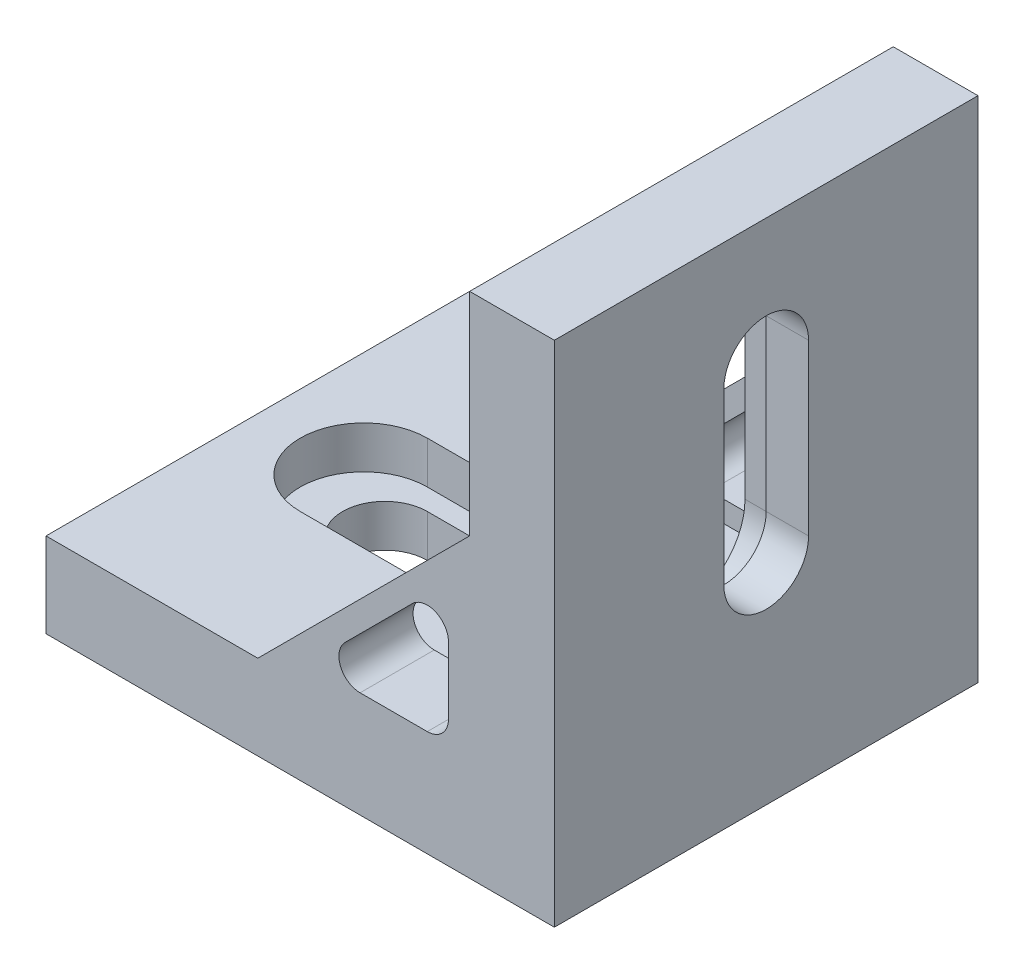
SolidWorks part; units mm, degrees
ref_plane "Front Plane" through (0, 0, 0) normal (0, 0, 1) x (1, 0, 0)
ref_plane "Top Plane" through (0, 0, 0) normal (0, 1, 0) x (1, 0, 0)
ref_plane "Right Plane" through (0, 0, 0) normal (1, 0, 0) x (0, 0, -1)
sketch "Sketch1" plane through (0, 0, 0) normal (0, 1, 0) x (1, 0, 0)
  line L0 (0, 10) -> (0, 0) construction
  line L1 (-10, -10) -> (10, -10)
  line L2 (-10, -10) -> (-10, 10)
  line L3 (-10, 10) -> (10, 10)
  line L4 (10, -10) -> (10, 10)
  line L5 (-10, -10) -> (10, 10) construction
  line L6 (-10, 10) -> (10, -10) construction
  line L7 (-4, 0) -> (4, 0) construction
  line L8 (-4, 2) -> (4, 2)
  line L9 (-4, -2) -> (4, -2)
  arc A0 (-4, 2) -> (-4, -2) centre (-4, 0) ccw
  arc A1 (4, -2) -> (4, 2) centre (4, 0) ccw
  point P0 (0, 0)
  point P10 (0, 0)
  dimension "D4" = 2
  dimension "D1" = 20
  dimension "D2" = 20
  dimension "D3" = 8
extrude "Boss-Extrude1" add sketch "Sketch1" along normal blind 4
sketch "Sketch3" plane through (0, 4, 0) normal (0, 1, 0) x (1, 0, 0)
  line L0 (-5, 0) -> (5, 0) construction
  line L1 (-5, 3) -> (5, 3)
  line L2 (-5, -3) -> (5, -3)
  arc A0 (-5, 3) -> (-5, -3) centre (-5, 0) ccw
  arc A1 (5, -3) -> (5, 3) centre (5, 0) ccw
  point P2 (0, 0)
  dimension "D2" = 3
  dimension "D1" = 10
extrude "Cut-Extrude1" cut sketch "Sketch3" against normal blind 2
sketch "Sketch4" plane through (10, 0, 0) normal (1, 0, 0) x (0, 0, -1)
  line L0 (0, 0) -> (0, 4) construction
  line L1 (-10, 4) -> (10, 4) construction
  line L3 (-10, 0) -> (10, 0)
  line L4 (-10, 0) -> (-10, 4)
  line L5 (-10, 4) -> (10, 4)
  line L6 (10, 0) -> (10, 4)
  line L7 (-10, 0) -> (10, 4) construction
  line L8 (-10, 4) -> (10, 0) construction
  point P5 (0, 2)
extrude "Boss-Extrude2" add sketch "Sketch4" along normal blind 4
sketch "Sketch5" plane through (0, 4, 0) normal (0, 1, 0) x (1, 0, 0)
  line L0 (14, 0) -> (8, 0) construction
  line L1 (14, 10) -> (14, -10) construction
  line L2 (-10, -10) -> (14, -10) construction
  line L3 (14, 10) -> (10, 10)
  line L4 (14, 10) -> (14, -10)
  line L5 (14, -10) -> (10, -10)
  line L6 (10, 10) -> (10, -10)
  arc A0 (5, -3) -> (5, 3) centre (5, 0) ccw construction
  dimension "D1" = 4
extrude "Boss-Extrude3" add sketch "Sketch5" along normal blind 20
sketch "Sketch6" plane through (10, 0, 0) normal (-1, 0, 0) x (0, 0, 1)
  line L0 (0, 24) -> (0, 4) construction
  line L1 (-10, 24) -> (10, 24) construction
  line L2 (-10, 4) -> (10, 4) construction
  line L3 (0, 9) -> (0, 19) construction
  line L4 (-3, 9) -> (-3, 19)
  line L5 (3, 9) -> (3, 19)
  arc A0 (-3, 9) -> (3, 9) centre (0, 9) ccw
  arc A1 (3, 19) -> (-3, 19) centre (0, 19) ccw
  point P8 (0, 14)
  dimension "D2" = 3
  dimension "D1" = 10
extrude "Cut-Extrude2" cut sketch "Sketch6" against normal blind 2
sketch "Sketch7" plane through (12, 0, 0) normal (-1, 0, 0) x (0, 0, 1)
  line L0 (0, 24) -> (0, 4) construction
  line L1 (-10, 24) -> (10, 24) construction
  line L2 (-10, 4) -> (10, 4) construction
  line L3 (0, 10) -> (0, 18) construction
  line L4 (-2, 10) -> (-2, 18)
  line L5 (2, 10) -> (2, 18)
  arc A0 (-2, 10) -> (2, 10) centre (0, 10) ccw
  arc A1 (2, 18) -> (-2, 18) centre (0, 18) ccw
  point P8 (0, 14)
  dimension "D2" = 2
  dimension "D1" = 8
extrude "Cut-Extrude3" cut sketch "Sketch7" against normal up to surface (2 mm away) up to face at (14, 12, 0)
sketch "Sketch16" plane through (0, 4, 0) normal (0, 1, 0) x (1, 0, 0)
  line L0 (0, 10) -> (10, 10) construction
  line L1 (10, 10) -> (-10, 10) construction
  line L2 (0, 10) -> (0, 3) construction
  line L3 (5, 3) -> (-5, 3) construction
  line L4 (0, 6.5) -> (10, 6.5)
  line L5 (10, 10) -> (10, -10) construction
ref_plane "Plane2" through (0, 0, -6.5) normal (0, 0, 1) x (1, 0, 0)
sketch "Sketch17" plane through (0, 0, -6.5) normal (0, 0, 1) x (1, 0, 0)
  line L9 (10, 4) -> (0, 4)
  line L10 (0, 4) -> (10, 4) construction
  line L11 (0, 4) -> (10, 4) construction
  line L12 (0, 4) -> (10, 14)
  line L13 (10, 24) -> (10, 4) construction
  line L14 (10, 14) -> (10, 4)
  dimension "D1" = 10
extrude "Extrude-Thin2" add sketch "Sketch17" against normal blind 3.5 thin
fillet "Fillet1" radius 1 3 edges at (2.4142, 5, -8.25) (9, 5, -8.25) (9, 11.5858, -8.25)
mirror "Mirror3" about plane through (0, 0, 0) normal (0, 0, 1) of "Fillet1", "Extrude-Thin2"
